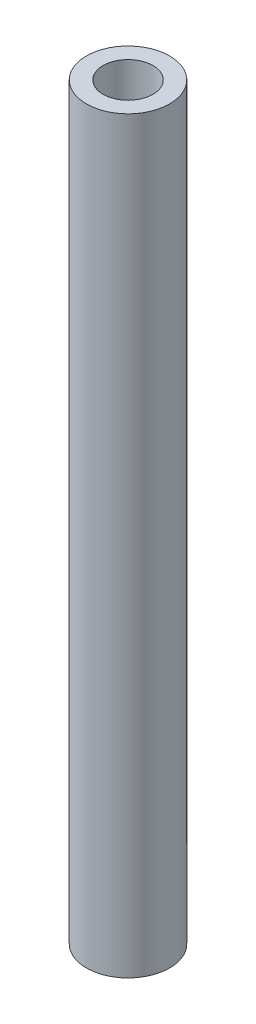
SolidWorks part; units mm, degrees
material "6061 合金"
ref_plane "前视基准面" through (0, 0, 0) normal (0, 0, 1) x (1, 0, 0)
ref_plane "上视基准面" through (0, 0, 0) normal (0, 1, 0) x (1, 0, 0)
ref_plane "右视基准面" through (0, 0, 0) normal (1, 0, 0) x (0, 0, -1)
other "Configuration Table"
sketch "草图1" plane through (0, 0, 0) normal (0, 1, 0) x (1, 0, 0)
  circle A0 centre (0, 0) radius 1.5
  circle A1 centre (0, 0) radius 2.5
  dimension "D1" = 5
  dimension "D2" = 3
extrude "凸台-拉伸1" add sketch "草图1" along normal blind 45
